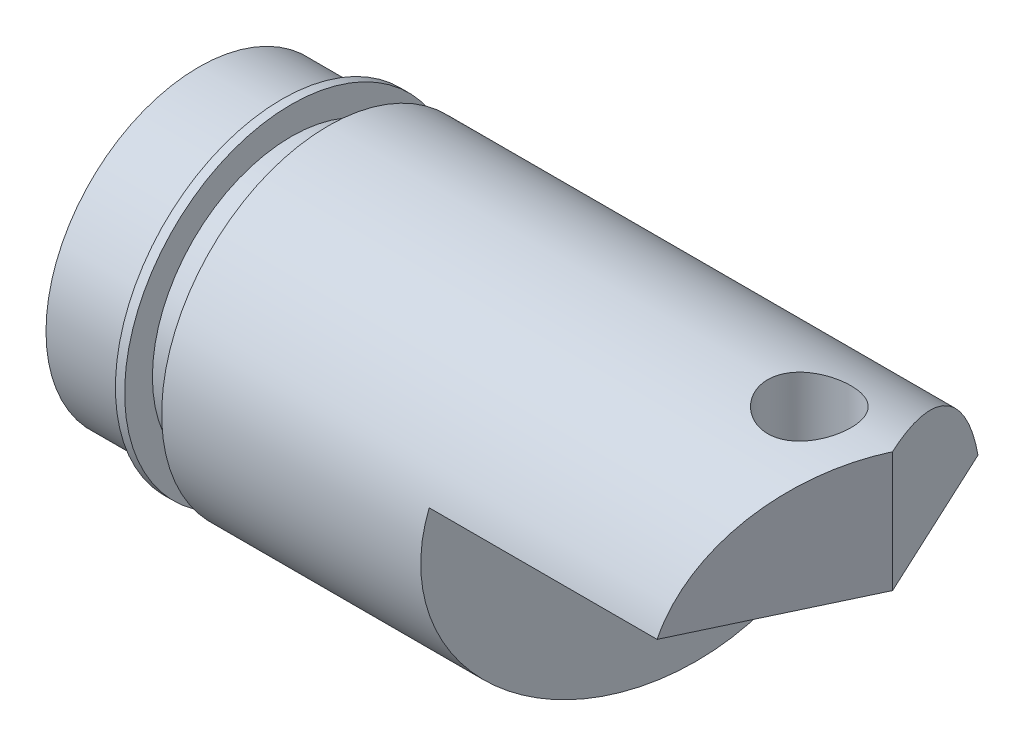
SolidWorks part; units mm, degrees
material "Acier allié inoxydable"
ref_plane "Plan de face" through (0, 0, 0) normal (0, 0, 1) x (1, 0, 0)
ref_plane "Plan de dessus" through (0, 0, 0) normal (0, 1, 0) x (1, 0, 0)
ref_plane "Plan de droite" through (0, 0, 0) normal (1, 0, 0) x (0, 0, -1)
sketch "Esquisse6" plane through (0, 0, 0) normal (0, 0, 1) x (1, 0, 0)
  line L0 (0, 21) -> (0, 33)
  line L1 (0, 33) -> (18, 33)
  line L2 (18, 33) -> (18, 36)
  line L3 (18, 36) -> (20, 36)
  line L4 (20, 36) -> (20, 30)
  line L5 (20, 30) -> (28, 30)
  line L6 (28, 30) -> (28, 36)
  line L7 (28, 36) -> (150, 36)
  line L8 (150, 36) -> (150, 0)
  line L9 (150, 0) -> (81, 0)
  line L10 (67.9217, 14.8764) -> (36, 19)
  line L11 (36, 19) -> (36, 21)
  line L12 (36, 21) -> (0, 21)
  arc A0 (81, 0) -> (67.9217, 14.8764) centre (66, 0) ccw
revolve "Révolution1" add sketch "Esquisse6" angle 360 about L9
ref_plane "Plan4" through (0, 10, 0) normal (0, 1, 0) x (-1, 0, 0)
sketch "Esquisse7" plane through (0, 10, 0) normal (0, 1, 0) x (1, 0, 0)
  line L0 (105, 36) -> (84, -36)
  line L1 (84, -36) -> (150, -36)
  line L2 (150, -36) -> (150, 36)
  line L3 (150, 36) -> (105, 36)
extrude "Enlèv. mat.-Extru.3" cut sketch "Esquisse7" against normal through all
sketch "Esquisse8" plane through (0, 10, 0) normal (0, 1, 0) x (-1, 0, 0)
  line L0 (-130.289, -42.2704) -> (-160.6635, -42.2704)
  line L1 (-160.6635, -42.2704) -> (-160.6635, 48.4838)
  line L2 (-160.6635, 48.4838) -> (-127.1253, 48.4838)
  line L3 (-127.1253, 48.4838) -> (-150, 0)
  line L4 (-150, 0) -> (-130.289, -42.2704)
  circle A0 centre (-132, 0) radius 9
extrude "Enlèv. mat.-Extru.4" cut sketch "Esquisse8" along normal through all
